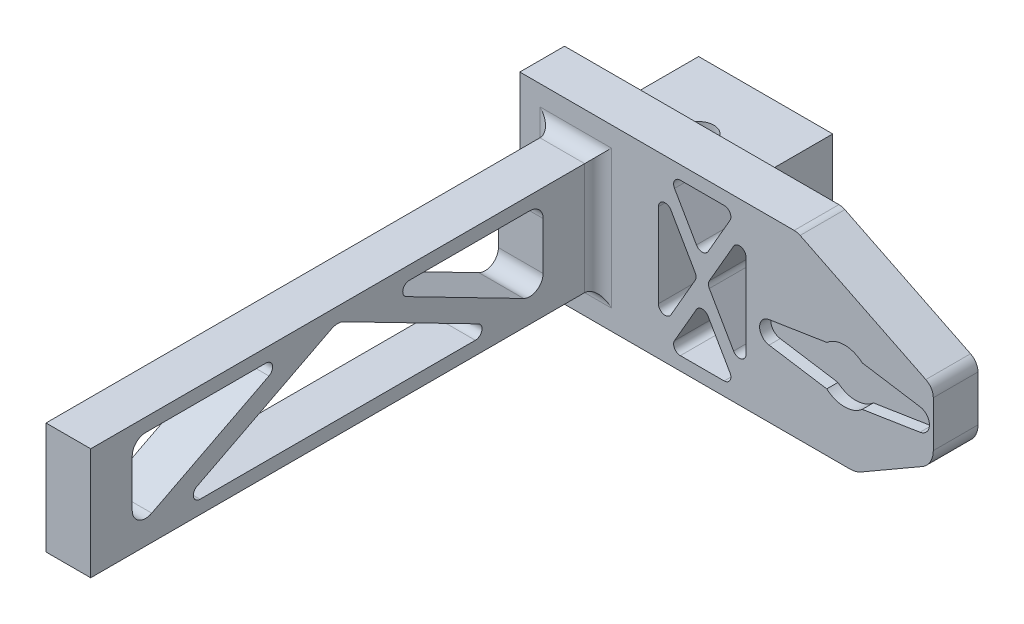
SolidWorks part; units mm, degrees
material "PLA"
ref_plane "Front Plane" through (0, 0, 0) normal (0, 0, 1) x (1, 0, 0)
ref_plane "Top Plane" through (0, 0, 0) normal (0, 1, 0) x (1, 0, 0)
ref_plane "Right Plane" through (0, 0, 0) normal (1, 0, 0) x (0, 0, -1)
sketch "Sketch3" plane through (0, 0, 0) normal (0, 0, 1) x (1, 0, 0)
  line L1 (-22.6388, -7.4411) -> (19.8612, -7.4411)
  line L2 (-22.6388, -7.4411) -> (-22.6388, 7.5589)
  line L3 (-22.6388, 7.5589) -> (19.8612, 7.5589)
  line L4 (19.8612, -7.4411) -> (19.8612, 7.5589)
  dimension "D1" = 15
  dimension "D2" = 42.5
extrude "Boss-Extrude1" add sketch "Sketch3" against normal blind 10
sketch "Sketch2" plane through (0, 0, 0) normal (0, 0, 1) x (1, 0, 0)
  line L0 (-16.8881, 2.4697) -> (-3.9686, 4.5)
  line L1 (-16.8881, -2.4697) -> (-3.9686, -4.5)
  line L2 (3.9686, 4.5) -> (16.8881, 2.4697)
  line L3 (16.8881, -2.4697) -> (3.9686, -4.5)
  line L4 (-16.9657, 2.9636) -> (-4.187, 4.9718)
  line L5 (4.187, 4.9718) -> (16.9657, 2.9636)
  line L6 (16.9657, -2.9636) -> (4.187, -4.9718)
  line L7 (-16.9657, -2.9636) -> (-4.187, -4.9718)
  arc A0 (-16.8881, 2.4697) -> (-16.8881, -2.4697) centre (-16.5, 0) ccw
  arc A1 (-3.9686, 4.5) -> (3.9686, 4.5) centre (0, 0) cw
  arc A2 (-3.9686, -4.5) -> (3.9686, -4.5) centre (0, 0) ccw
  arc A3 (16.8881, -2.4697) -> (16.8881, 2.4697) centre (16.5, 0) ccw
  arc A4 (-4.187, 4.9718) -> (4.187, 4.9718) centre (0, 0) cw
  arc A5 (16.9657, -2.9636) -> (16.9657, 2.9636) centre (16.5, 0) ccw
  arc A6 (-4.187, -4.9718) -> (4.187, -4.9718) centre (0, 0) ccw
  arc A7 (-16.9657, 2.9636) -> (-16.9657, -2.9636) centre (-16.5, 0) ccw
  dimension "D1" = 0.5
extrude "Cut-Extrude1" cut sketch "Sketch2" against normal blind 2.5 contours L3 A2 L1 A0 L0 A1 L2 A3
sketch "Sketch11" plane through (0, -7.4411, 0) normal (0, -1, 0) x (1, 0, 0)
  line L0 (8.25, 0) -> (-8.25, 0) construction
  line L1 (19.8612, -10) -> (-22.6388, -10)
  line L2 (19.8612, -10) -> (19.8612, 0)
  line L3 (19.8612, 0) -> (-22.6388, 0)
  line L4 (-22.6388, -10) -> (-22.6388, 0)
  line L5 (-22.6388, -10) -> (-22.6388, 0) construction
extrude "Boss-Extrude5" add sketch "Sketch11" along normal blind 10
sketch "Sketch14" plane through (0, 7.5589, 0) normal (0, 1, 0) x (1, 0, 0)
  line L0 (-8.25, 0) -> (8.25, 0) construction
  line L1 (19.8612, 10) -> (-22.6388, 10)
  line L2 (19.8612, 10) -> (19.8612, 0)
  line L3 (19.8612, 0) -> (-22.6388, 0)
  line L4 (-22.6388, 10) -> (-22.6388, 0)
  line L5 (-22.6388, 10) -> (-22.6388, 0) construction
extrude "Boss-Extrude7" add sketch "Sketch14" along normal blind 15
sketch "Sketch20" plane through (-22.6388, 0, 0) normal (-1, 0, 0) x (0, 0, 1)
  line L0 (0, -8.25) -> (0, 8.25) construction
  line L1 (-10, 22.5589) -> (0, 22.5589)
  line L2 (-10, 22.5589) -> (-10, -17.4411)
  line L3 (-10, -17.4411) -> (0, -17.4411)
  line L4 (0, 22.5589) -> (0, -17.4411)
  line L5 (0, -17.4411) -> (-10, -17.4411) construction
extrude "Boss-Extrude10" add sketch "Sketch20" along normal blind 50
sketch "Sketch21" plane through (0, 0, 0) normal (0, 0, 1) x (1, 0, 0)
  line L1 (-65.1388, 15.0589) -> (-55.1388, 15.0589)
  line L2 (-65.1388, 15.0589) -> (-65.1388, -9.9411)
  line L3 (-65.1388, -9.9411) -> (-55.1388, -9.9411)
  line L4 (-55.1388, 15.0589) -> (-55.1388, -9.9411)
  line L5 (-72.6388, 22.5589) -> (19.8612, 22.5589) construction
  line L6 (-72.6388, -17.4411) -> (-72.6388, 22.5589) construction
  dimension "D1" = 7.5
  dimension "D2" = 25
  dimension "D3" = 7.5
  dimension "D4" = 10
extrude "Boss-Extrude11" add sketch "Sketch21" along normal blind 113.5
sketch "Sketch22" plane through (0, 0, -10) normal (0, 0, -1) x (-1, 0, 0)
  line L0 (72.6388, 22.5589) -> (72.6388, -17.4411) construction
  line L1 (42.6388, 5.5589) -> (72.6388, 5.5589)
  line L2 (42.6388, 5.5589) -> (42.6388, -0.4411)
  line L3 (42.6388, -0.4411) -> (72.6388, -0.4411)
  line L4 (72.6388, 5.5589) -> (72.6388, -0.4411)
  line L5 (42.6388, 5.5589) -> (72.6388, -0.4411) construction
  line L6 (42.6388, -0.4411) -> (72.6388, 5.5589) construction
  line L7 (72.6388, -17.4411) -> (-19.8612, -17.4411) construction
  point P0 (57.6388, 2.5589)
  dimension "D1" = 20
  dimension "D2" = 30
  dimension "D3" = 6
extrude "Boss-Extrude12" add sketch "Sketch22" along normal blind 30
sketch "Sketch23" plane through (0, -0.4411, 0) normal (0, -1, 0) x (1, 0, 0)
  line L1 (-72.6388, -10) -> (-42.6388, -10)
  line L2 (-72.6388, -10) -> (-72.6388, -40)
  line L3 (-72.6388, -40) -> (-42.6388, -40)
  line L4 (-42.6388, -10) -> (-42.6388, -40)
extrude "Boss-Extrude13" add sketch "Sketch23" along normal blind 8.5
fillet "Fillet1" radius 3 4 edges at (-60.1388, 15.0589, 0) (-65.1388, 2.5589, 0) (-55.1388, 2.5589, 0) (-60.1388, -9.9411, 0)
chamfer "Chamfer1" distance 15 angle 63.75 1 edges at (19.8612, 22.5589, -5)
fillet "Fillet2" radius 3 2 edges at (-10.5558, 22.5589, -5) (19.8612, 7.5589, -5)
chamfer "Chamfer2" distance 10 angle 60 1 edges at (19.8612, -17.4411, -5)
fillet "Fillet3" radius 5 2 edges at (2.5406, -17.4411, -5) (19.8612, -7.4411, -5)
sketch "Sketch24" plane through (-65.1388, 0, 0) normal (-1, 0, 0) x (0, 0, 1)
  line L0 (58.25, 15.0589) -> (58.25, -9.9411) construction
  line L1 (113.5, 15.0589) -> (3, 15.0589) construction
  line L2 (113.5, -9.9411) -> (3, -9.9411) construction
  line L3 (58.25, -6.9411) -> (95.25, -6.9411)
  line L4 (58.25, -6.9411) -> (21.25, -6.9411)
  line L5 (21.25, -6.9411) -> (58.25, 12.0589)
  line L6 (58.25, 12.0589) -> (95.25, -6.9411)
  line L7 (48.399, 12.0589) -> (12.29, -6.4835)
  line L8 (48.399, 12.0589) -> (12.29, 12.0589)
  line L9 (12.29, 12.0589) -> (12.29, -6.4835)
  line L10 (68.101, 12.0589) -> (104.21, 12.0589)
  line L11 (68.101, 12.0589) -> (104.21, -6.4835)
  line L12 (104.21, 12.0589) -> (104.21, -6.4835)
  dimension "D1" = 37
  dimension "D2" = 37
  dimension "D3" = 3
  dimension "D4" = 3
  dimension "D5" = 3
  dimension "D6" = 4.5
  dimension "D7" = 18.5424
extrude "Cut-Extrude2" cut sketch "Sketch24" against normal through all
fillet "Fillet4" radius 3 5 edges at (-60.1388, -6.4835, 12.29) (-60.1388, 12.0589, 12.29) (-60.1388, -6.4835, 104.21) (-60.1388, 12.0589, 104.21) (-60.1388, 12.0589, 58.25)
fillet "Fillet5" radius 1.5 4 edges at (-60.1388, 12.0589, 68.101) (-60.1388, -6.9411, 95.25) (-60.1388, -6.9411, 21.25) (-60.1388, 12.0589, 48.399)
sketch "Sketch30" plane through (0, 5.5589, 0) normal (0, 1, 0) x (1, 0, 0)
  line L0 (-72.6388, 40) -> (-42.6388, 10) construction
  line L1 (-42.6388, 40) -> (-72.6388, 10) construction
  point P10 (-57.6388, 25)
hole_wizard "M8 Tapped Hole1" positions "Sketch30" profile "Sketch31" tap size "M8" standard "ISO"
sketch "Sketch31" plane through (-57.6388, 5.5589, -25) normal (1, 0, 0) x (0, 0, 1)
  line L0 (0, 0) -> (0, 24.2929)
  line L1 (0, 24.2929) -> (3.4, 22.25)
  line L2 (3.4, 22.25) -> (3.4, 0)
  line L5 (3.4, 0) -> (0, 0)
  line L10 (0, 24.2929) -> (-3.4, 22.25) construction
  line L11 (0, -6.35) -> (0, 107.95) construction
  dimension "Tap Drill Dia." = 6.8
  dimension "Tap Drill Depth" = 22.25
  dimension "Drill Angle" = 118
cosmetic thread "Hole Thread1" parameters "D1"=16, "D2"=8
ref_plane "Plane1" through (-42.6388, 5.5589, -10) normal (0, 0, 1) x (1, 0, 0)
sketch "Sketch32" plane through (-42.6388, 5.5589, -10) normal (0, 0, 1) x (1, 0, 0)
  line L0 (31.3835, 17) -> (-30, 17) construction
  line L1 (1, 14) -> (20.6191, 14) construction
  line L2 (1, 14) -> (1, -20) construction
  line L3 (1, -20) -> (20.6191, -20) construction
  line L4 (20.6191, 14) -> (20.6191, -20) construction
  line L5 (-30, -23) -> (43.8397, -23) construction
  line L6 (0, 0) -> (0, -14.5) construction
  line L7 (20.6191, 14) -> (1, -20) construction
  line L8 (20.6191, -20) -> (1, 14) construction
  line L9 (10.8096, 14) -> (3.3096, 14)
  line L10 (3.3096, 14) -> (10.8096, 1.0025)
  line L11 (10.8096, 1.0025) -> (18.3096, 14)
  line L12 (18.3096, 14) -> (10.8096, 14)
  line L13 (1, 12) -> (9.6555, -3)
  line L14 (9.6555, -3) -> (1, -18)
  line L15 (1, -18) -> (1, -3)
  line L16 (1, -3) -> (1, 12)
  line L17 (20.6191, -3) -> (1, -3) construction
  line L18 (10.8096, -20) -> (10.8096, 14) construction
  line L19 (10.8096, -7.0025) -> (18.3096, -20)
  line L20 (3.3096, -20) -> (10.8096, -7.0025)
  line L21 (10.8096, -20) -> (3.3096, -20)
  line L22 (18.3096, -20) -> (10.8096, -20)
  line L23 (20.6191, -18) -> (20.6191, -3)
  line L24 (11.9636, -3) -> (20.6191, -18)
  line L25 (20.6191, 12) -> (11.9636, -3)
  line L26 (20.6191, -3) -> (20.6191, 12)
  dimension "D1" = 3
  dimension "D2" = 3
  dimension "D3" = 1
  dimension "D4" = 7.5
  dimension "D5" = 7.5
  dimension "D6" = 3
  dimension "D7" = 15
  dimension "D8" = 15
extrude "Cut-Extrude3" cut sketch "Sketch32" along normal through all
fillet "Fillet6" radius 1.5 12 edges at (-41.6388, 17.5589, -5) (-31.8293, 6.5614, -5) (-39.3293, 19.5589, -5) (-24.3293, 19.5589, -5) (-22.0197, -12.4411, -5) (-22.0197, 17.5589, -5) (-30.6752, 2.5589, -5) (-39.3293, -14.4411, -5) (-24.3293, -14.4411, -5) (-31.8293, -1.4436, -5) (-41.6388, -12.4411, -5) (-32.9834, 2.5589, -5)
